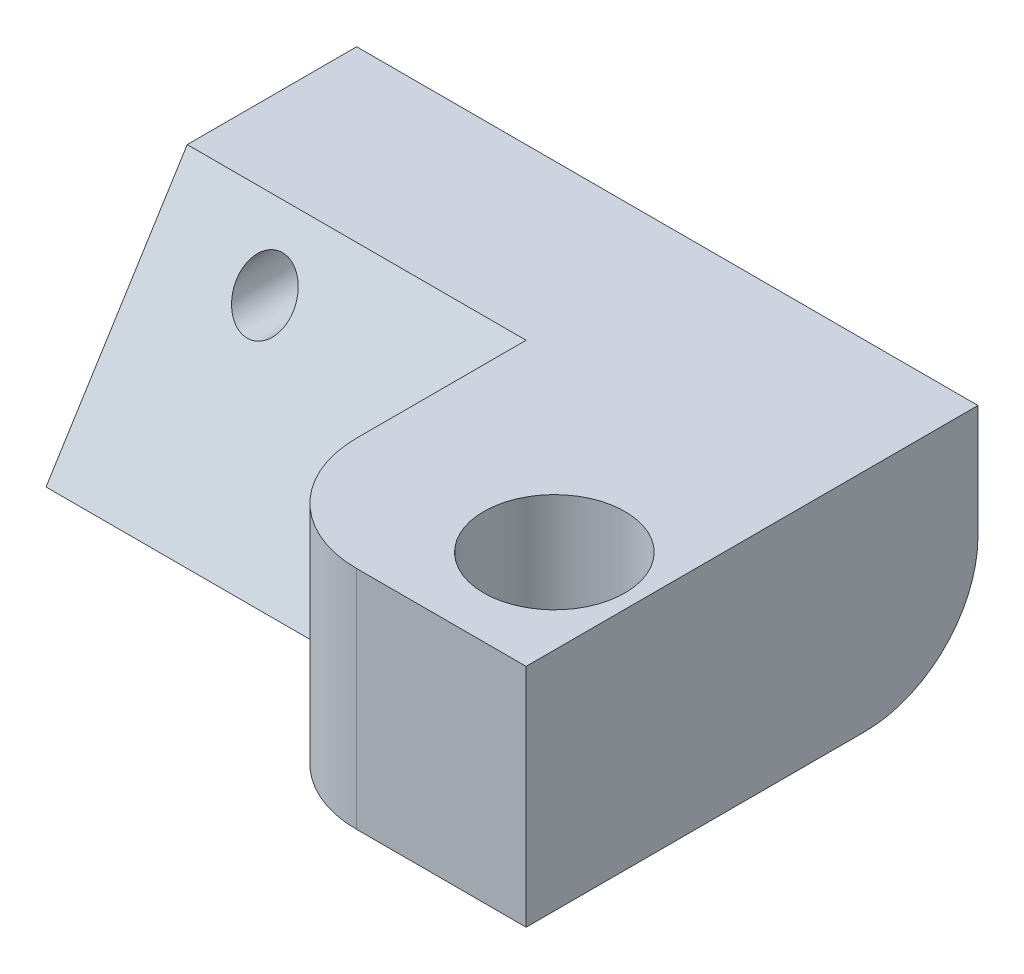
SolidWorks part; units mm, degrees
ref_plane "Front Plane" through (0, 0, 0) normal (0, 0, 1) x (1, 0, 0)
ref_plane "Top Plane" through (0, 0, 0) normal (0, 1, 0) x (1, 0, 0)
ref_plane "Right Plane" through (0, 0, 0) normal (1, 0, 0) x (0, 0, -1)
sketch "Sketch2" plane through (0, 0, 0) normal (0, 1, 0) x (1, 0, 0)
  line L0 (76.2, -101.6) -> (0, -101.6)
  line L1 (0, 0) -> (139.7, 0)
  line L2 (0, 0) -> (0, -50.8)
  line L4 (139.7, 0) -> (139.7, -28.8213)
  line L5 (0, -101.6) -> (0, -50.8)
  line L6 (139.7, -28.8213) -> (139.7, -101.6)
  line L7 (139.7, -101.6) -> (76.2, -101.6)
  dimension "D1" = 139.7
  dimension "D2" = 63.5
  dimension "D3" = 101.6
  dimension "D4" = 50.8
extrude "Boss-Extrude3" add sketch "Sketch2" along normal blind 50.8
sketch "Sketch5" plane through (0, 0, 0) normal (-1, 0, 0) x (0, 0, 1)
  line L0 (69.85, 0) -> (101.6, 0)
  line L1 (0, 0) -> (101.6, 0) construction
  line L2 (101.6, 0) -> (101.6, 50.8)
  line L4 (0, 50.8) -> (101.6, 50.8) construction
  line L5 (69.85, 0) -> (38.1, 50.8)
  line L6 (101.6, 50.8) -> (38.1, 50.8)
extrude "Cut-Extrude1" cut sketch "Sketch5" against normal blind 76.2
sketch "Sketch7" plane through (0, 0, 0) normal (0, 0, -1) x (-1, 0, 0)
  circle A0 centre (-25.4, 38.1) radius 6.35
  dimension "D3" = 12.7
  dimension "D1" = 25.4
  dimension "D2" = 12.7
extrude "Cut-Extrude2" cut sketch "Sketch7" against normal blind 76.2
sketch "Sketch8" plane through (0, 50.8, 0) normal (0, 1, 0) x (1, 0, 0)
  circle A0 centre (120.65, -76.2) radius 9.525
  dimension "D3" = 19.05
  dimension "D1" = 19.05
  dimension "D2" = 25.4
extrude "Cut-Extrude3" cut sketch "Sketch8" against normal blind 76.2
sketch "Sketch9" plane through (0, 50.8, 0) normal (0, 1, 0) x (1, 0, 0)
  circle A0 centre (120.65, -76.2) radius 15.875
  dimension "D1" = 31.75
extrude "Cut-Extrude4" cut sketch "Sketch9" against normal blind 25.4
fillet "Fillet1" radius 25.4 2 edges at (76.2, 25.4, 101.6) (69.85, 0, 0)
